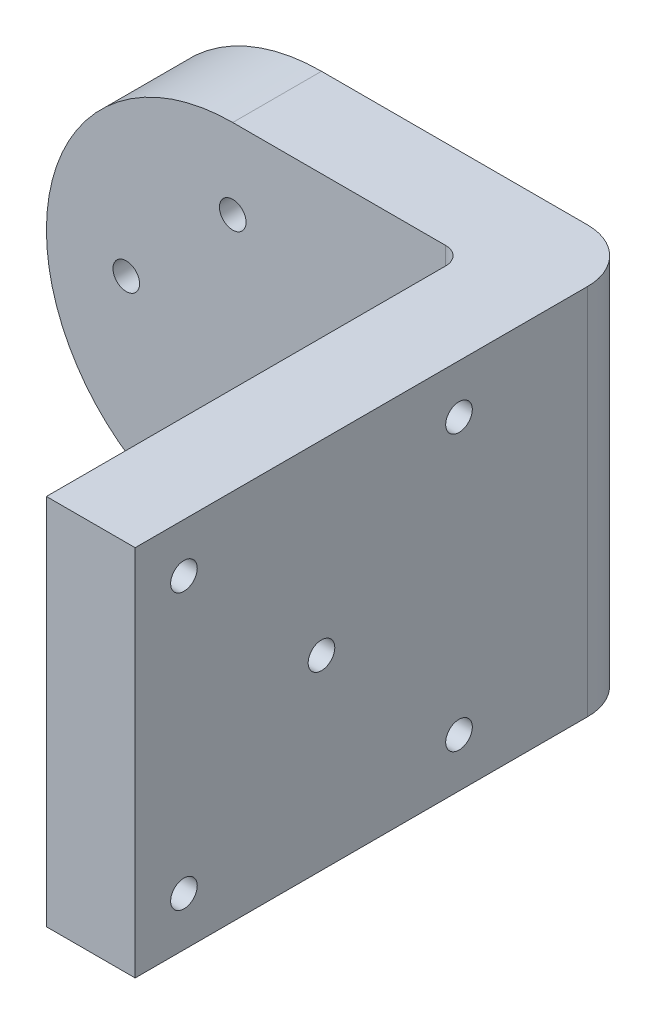
SolidWorks part; units mm, degrees
ref_plane "前视基准面" through (0, 0, 0) normal (0, 0, 1) x (1, 0, 0)
ref_plane "上视基准面" through (0, 0, 0) normal (0, 1, 0) x (1, 0, 0)
ref_plane "右视基准面" through (0, 0, 0) normal (1, 0, 0) x (0, 0, -1)
sketch "草图1" plane through (0, 0, 0) normal (0, 0, 1) x (1, 0, 0)
  line L0 (0, 0) -> (36.6723, 0) construction
  line L1 (0, 0) -> (0, 24.0559) construction
  line L2 (0, 21) -> (0, -21)
  line L3 (0, 21) -> (21, 21)
  line L4 (0, -21) -> (21, -21)
  line L5 (21, 21) -> (21, -21)
  line L6 (21, 21) -> (21, -21)
  line L7 (21, 21) -> (26, 21)
  line L8 (21, -21) -> (26, -21)
  line L9 (26, 21) -> (26, -21)
  circle A0 centre (0, 0) radius 21
  circle A1 centre (0, 0) radius 12
  circle A2 centre (0, 12) radius 1.5
  circle A3 centre (12, 0) radius 1.5
  circle A4 centre (-12, 0) radius 1.5
  circle A5 centre (0, -12) radius 1.5
  dimension "D1" = 42
  dimension "D2" = 24
  dimension "D3" = 3
  dimension "D4" = 5
extrude "凸台-拉伸1" add sketch "草图1" along normal blind 10
sketch "草图2" plane through (26, 0, 0) normal (1, 0, 0) x (0, 0, -1)
  line L0 (-15, 21) -> (-15, -21)
  line L1 (-15, 21) -> (-57, 21)
  line L2 (-15, -21) -> (-57, -21)
  line L3 (-57, 21) -> (-57, -21)
  line L4 (-57, 21) -> (-15, -21)
  line L5 (-15, 21) -> (-57, -21)
  line L12 (-10, 21) -> (-15, 21)
  line L13 (-10, 21) -> (-10, -21)
  line L14 (-10, -21) -> (-15, -21)
  line L15 (-15, 21) -> (-15, -21)
  circle A0 centre (-36, 0) radius 1.5
  circle A1 centre (-51.5, 15.5) radius 1.5
  circle A2 centre (-20.5, 15.5) radius 1.5
  circle A3 centre (-20.5, -15.5) radius 1.5
  circle A4 centre (-51.5, -15.5) radius 1.5
  point P16 (0, 0)
  point P17 (0, 0)
  point P18 (0, 0)
  line M10 (0, -21) -> (0, 21)
  line M11 (0, 21) -> (-10, 21)
  line M12 (-10, 21) -> (-10, -21)
  line M13 (-10, -21) -> (0, -21)
  dimension "D2" = 3
  dimension "D1" = 42
  dimension "D3" = 31
  dimension "D4" = 5
extrude "凸台-拉伸2" add sketch "草图2" along normal blind 10 contours A2 L5 L1 L4 A1 A0 | A3 L4 L5 A2 A0 M12 | A4 L5 A0 L4 A1 L3 | A4 L5 L2 L4 A3 A0 | M13 M10 M11 M12
fillet "圆角1" radius 2 1 edges at (26, 0, 10)
fillet "圆角2" radius 6 1 edges at (36, 0, 0)
